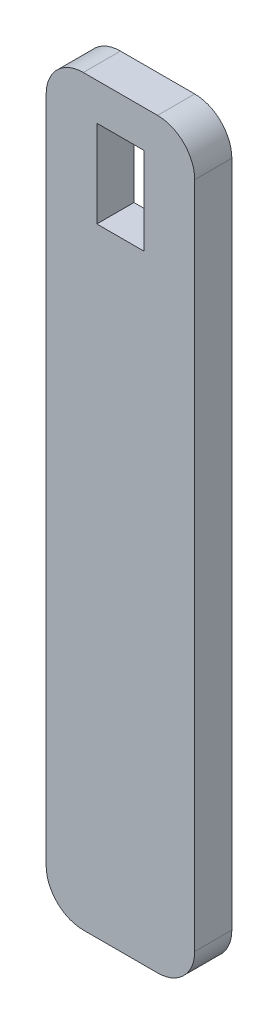
SolidWorks part; units mm, degrees
ref_plane "Přední rovina" through (0, 0, 0) normal (0, 0, 1) x (1, 0, 0)
ref_plane "Horní rovina" through (0, 0, 0) normal (0, 1, 0) x (1, 0, 0)
ref_plane "Pravá rovina" through (0, 0, 0) normal (1, 0, 0) x (0, 0, -1)
sketch "Skica1" plane through (0, 0, 0) normal (0, 0, 1) x (1, 0, 0)
  line L1 (0, 0) -> (40, 0)
  line L2 (0, 0) -> (0, 200)
  line L3 (0, 200) -> (40, 200)
  line L4 (40, 0) -> (40, 200)
  dimension "D1" = 200
  dimension "D2" = 40
extrude "Přidat vysunutím1" add sketch "Skica1" along normal blind 10
fillet "Zaoblit1" radius 10 4 edges at (40, 0, 5) (0, 0, 5) (40, 200, 5) (0, 200, 5)
sketch "Skica2" plane through (0, 0, 10) normal (0, 0, 1) x (1, 0, 0)
  line L1 (13.65, 190) -> (26.35, 190)
  line L2 (13.65, 190) -> (13.65, 166.5)
  line L3 (13.65, 166.5) -> (26.35, 166.5)
  line L4 (26.35, 190) -> (26.35, 166.5)
  line L5 (30, 200) -> (10, 200) construction
  point P4 (20, 200)
  point P7 (20, 190)
  dimension "D1" = 12.7
  dimension "D2" = 23.5
  dimension "D3" = 10
extrude "Odebrat vysunutím1" cut sketch "Skica2" against normal through all
